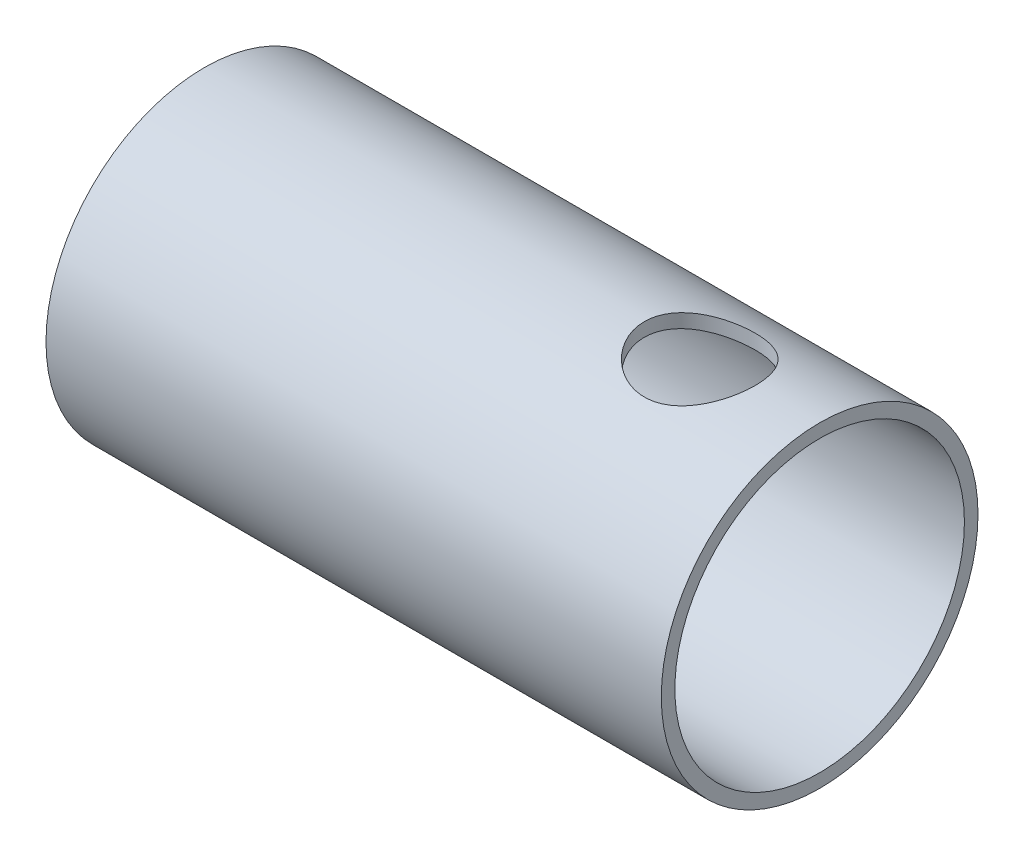
SolidWorks part; units mm, degrees
material "Acrylic (Medium-high impact)"
ref_plane "Front Plane" through (0, 0, 0) normal (0, 0, 1) x (1, 0, 0)
ref_plane "Top Plane" through (0, 0, 0) normal (0, 1, 0) x (1, 0, 0)
ref_plane "Right Plane" through (0, 0, 0) normal (1, 0, 0) x (0, 0, -1)
sketch "Sketch3" plane through (0, 0, 0) normal (1, 0, 0) x (0, 0, -1)
  circle A0 centre (0, 0) radius 32
  circle A1 centre (0, 0) radius 35
  dimension "D1" = 70
  dimension "D2" = 64
extrude "Boss-Extrude1" add sketch "Sketch3" along normal mid plane 136
sketch "Sketch4" plane through (0, 0, 0) normal (0, 1, 0) x (1, 0, 0)
  line L1 (-41.5, 0) -> (0, 0) construction
  line L2 (-68, 35) -> (-68, -35) construction
  circle A0 centre (-41.5, 0) radius 12.25
  dimension "D1" = 24.5
  dimension "D2" = 26.5
extrude "Cut-Extrude1" cut sketch "Sketch4" against normal through all
sketch "Sketch5" plane through (0, 0, 0) normal (0, 1, 0) x (1, 0, 0)
  line L0 (0, 0) -> (41.5, 0) construction
  line L1 (68, -35) -> (68, 35) construction
  circle A0 centre (41.5, 0) radius 12.25
  dimension "D1" = 24.5
  dimension "D2" = 26.5
extrude "Cut-Extrude2" cut sketch "Sketch5" along normal through all
